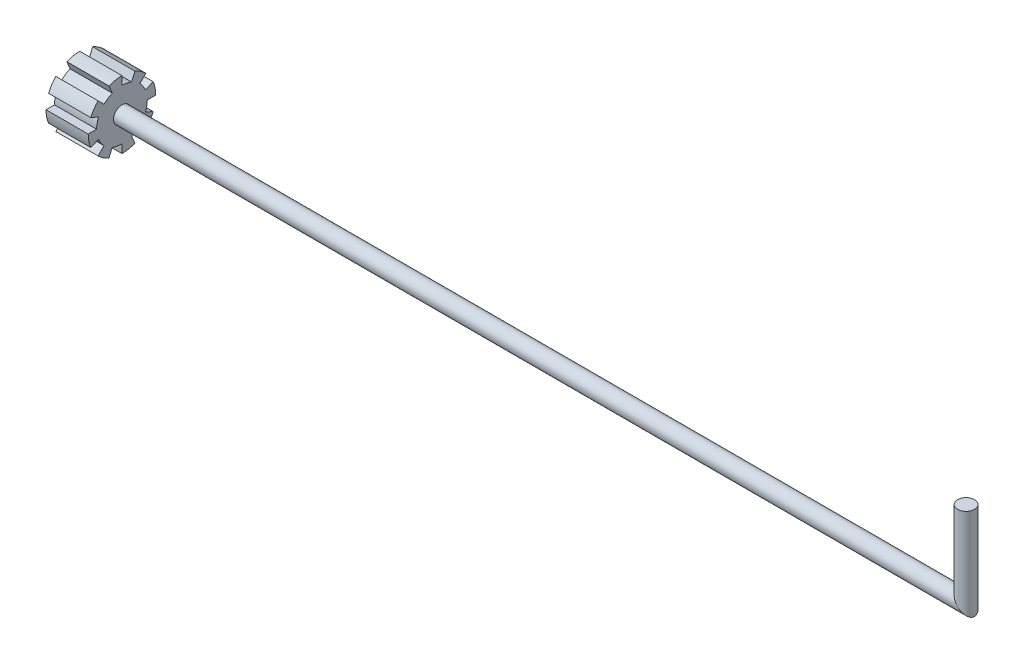
SolidWorks part; units mm, degrees
ref_plane "Ön Düzlem" through (0, 0, 0) normal (0, 0, 1) x (1, 0, 0)
ref_plane "Üst Düzlem" through (0, 0, 0) normal (0, 1, 0) x (1, 0, 0)
ref_plane "Sağ Düzlem" through (0, 0, 0) normal (1, 0, 0) x (0, 0, -1)
sketch "Çizim1" plane through (0, 0, 0) normal (1, 0, 0) x (0, 0, -1)
  circle A0 centre (0, 0) radius 4
  dimension "D1" = 8
extrude "Yükseklik-Ekstrüzyon1" add sketch "Çizim1" along normal blind 5
sketch "Çizim2" plane through (0, 0, 0) normal (1, 0, 0) x (0, 0, -1)
  line L0 (0, 3) -> (0, 4)
  line L1 (1.1481, 2.7716) -> (1.5307, 3.6955)
  line L2 (2.1213, 2.1213) -> (2.8284, 2.8284)
  line L3 (2.7716, 1.1481) -> (3.6955, 1.5307)
  line L4 (3, 0) -> (4, 0)
  line L5 (2.7716, -1.1481) -> (3.6955, -1.5307)
  line L6 (2.1213, -2.1213) -> (2.8284, -2.8284)
  line L7 (1.1481, -2.7716) -> (1.5307, -3.6955)
  line L8 (0, -3) -> (0, -4)
  line L9 (-1.1481, -2.7716) -> (-1.5307, -3.6955)
  line L10 (-2.1213, -2.1213) -> (-2.8284, -2.8284)
  line L11 (-2.7716, -1.1481) -> (-3.6955, -1.5307)
  line L12 (-3, 0) -> (-4, 0)
  line L13 (-2.7716, 1.1481) -> (-3.6955, 1.5307)
  line L14 (-2.1213, 2.1213) -> (-2.8284, 2.8284)
  line L15 (-1.1481, 2.7716) -> (-1.5307, 3.6955)
  arc A0 (-3.6955, 1.5307) -> (-4, 0) centre (0, 0) ccw
  arc A1 (-2.7716, 1.1481) -> (-3, 0) centre (0, 0) ccw
  arc A2 (-1.1481, 2.7716) -> (-2.1213, 2.1213) centre (0, 0) ccw
  arc A3 (-1.5307, 3.6955) -> (-2.8284, 2.8284) centre (0, 0) ccw
  arc A4 (1.1481, 2.7716) -> (0, 3) centre (0, 0) ccw
  arc A5 (1.5307, 3.6955) -> (0, 4) centre (0, 0) ccw
  arc A6 (2.7716, 1.1481) -> (2.1213, 2.1213) centre (0, 0) ccw
  arc A7 (3.6955, 1.5307) -> (2.8284, 2.8284) centre (0, 0) ccw
  arc A8 (2.7716, -1.1481) -> (3, 0) centre (0, 0) ccw
  arc A9 (3.6955, -1.5307) -> (4, 0) centre (0, 0) ccw
  arc A10 (1.1481, -2.7716) -> (2.1213, -2.1213) centre (0, 0) ccw
  arc A11 (1.5307, -3.6955) -> (2.8284, -2.8284) centre (0, 0) ccw
  arc A12 (-1.1481, -2.7716) -> (0, -3) centre (0, 0) ccw
  arc A13 (-1.5307, -3.6955) -> (0, -4) centre (0, 0) ccw
  arc A14 (-2.7716, -1.1481) -> (-2.1213, -2.1213) centre (0, 0) ccw
  arc A15 (-3.6955, -1.5307) -> (-2.8284, -2.8284) centre (0, 0) ccw
  point P22 (0, 0)
  dimension "D2" = 6
  dimension "D3" = 8
  dimension "D1" = 16
extrude "Kes-Ekstrüzyon1" cut sketch "Çizim2" along normal blind 5
sketch "Çizim3" plane through (5, 0, 0) normal (1, 0, 0) x (0, 0, -1)
  circle A0 centre (0, 0) radius 1
  dimension "D1" = 2
sketch "Çizim4" plane through (0, 0, 0) normal (0, 0, 1) x (1, 0, 0)
  line L0 (5, 0) -> (105, 0)
  line L1 (5, -1) -> (5, 1) construction
  line L2 (105, 0) -> (105, 10)
  dimension "D2" = 10
  dimension "D1" = 100
sweep "Süpür1" add profiles "Çizim3" path "Çizim4"
